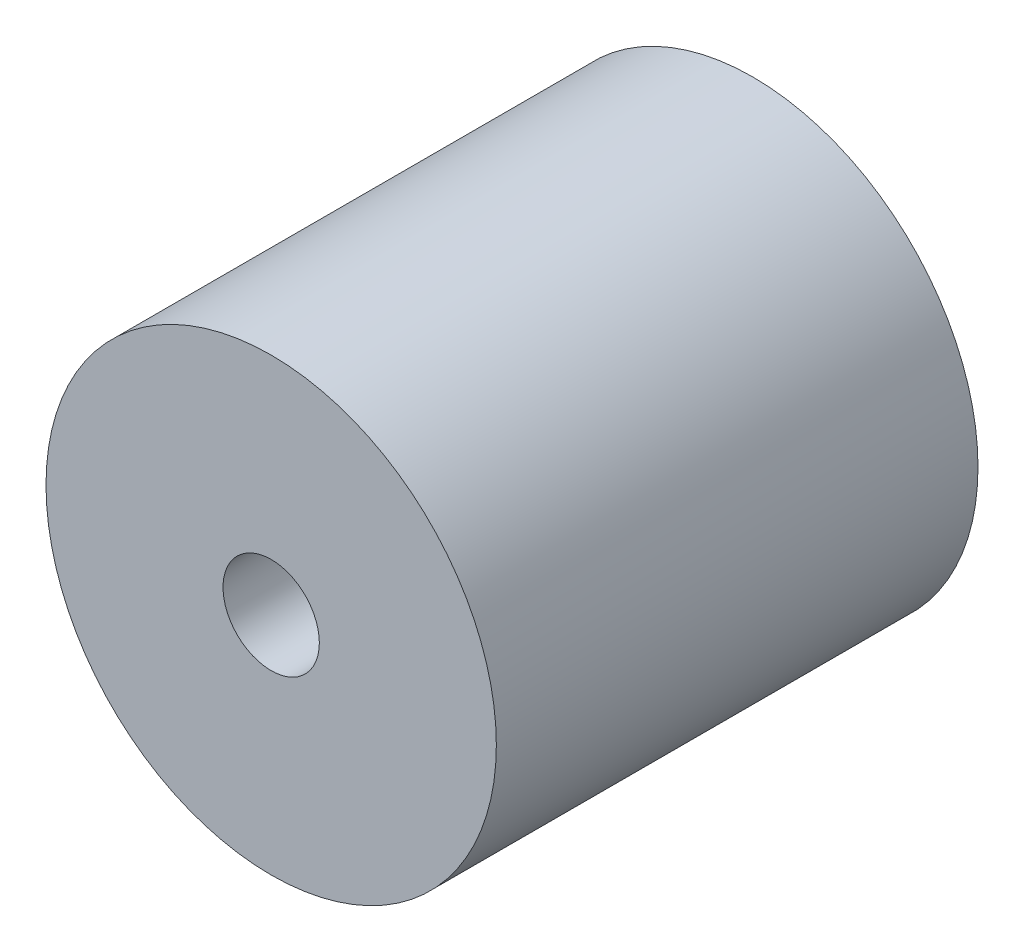
SolidWorks part; units mm, degrees
material "BUTYL"
ref_plane "前视基准面" through (0, 0, 0) normal (0, 0, 1) x (1, 0, 0)
ref_plane "上视基准面" through (0, 0, 0) normal (0, 1, 0) x (1, 0, 0)
ref_plane "右视基准面" through (0, 0, 0) normal (1, 0, 0) x (0, 0, -1)
sketch "草图1" plane through (0, 0, 0) normal (0, 0, 1) x (1, 0, 0)
  circle A0 centre (0, 0) radius 9.35
  dimension "D1" = 18.7
ref_plane "基准面1" through (0, 0, 8.75) normal (0, 0, 1) x (1, 0, 0)
ref_plane "基准面2" through (0, 0, -9.95) normal (0, 0, 1) x (1, 0, 0)
extrude "凸台-拉伸1" add sketch "草图1" along normal blind 20
sketch "草图5" plane through (0, 0, 20) normal (0, 0, 1) x (1, 0, 0)
  circle A0 centre (0, 0) radius 2
  dimension "D1" = 4
extrude "切除-拉伸2" cut sketch "草图5" against normal blind 20
